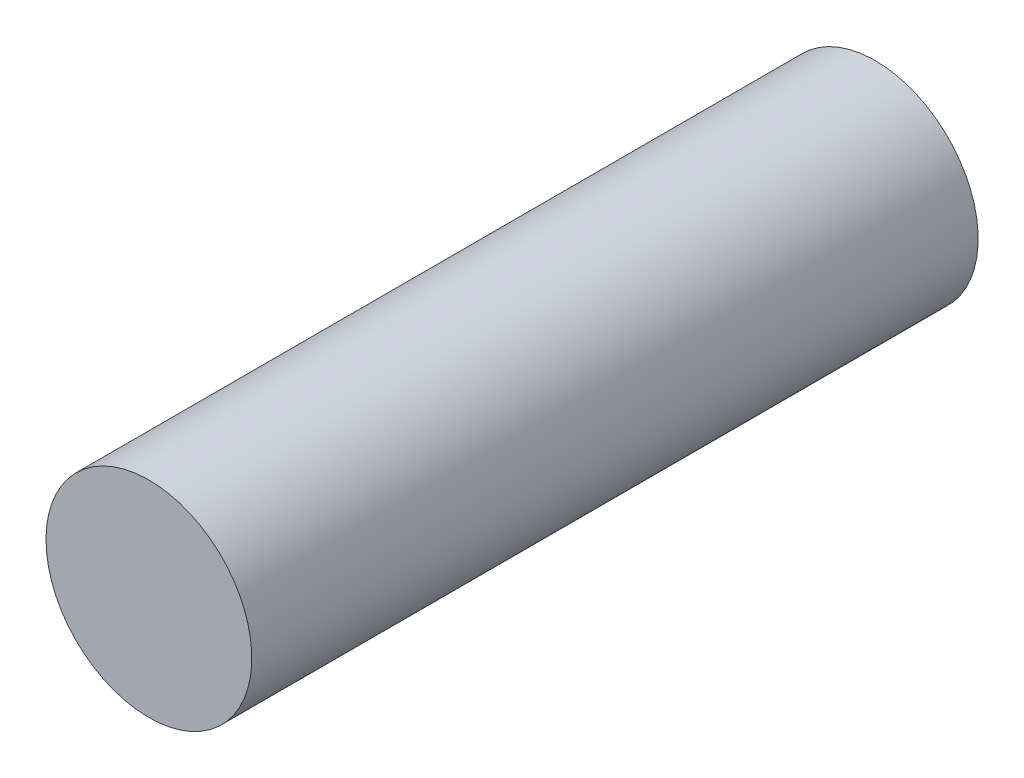
SolidWorks part; units mm, degrees
ref_plane "Front" through (0, 0, 0) normal (0, 0, 1) x (1, 0, 0)
ref_plane "Top" through (0, 0, 0) normal (0, 1, 0) x (1, 0, 0)
ref_plane "Right" through (0, 0, 0) normal (1, 0, 0) x (0, 0, -1)
sketch "Sketch1" plane through (0, 0, 0) normal (0, 0, 1) x (1, 0, 0)
  circle A0 centre (0, 0) radius 12.75
  dimension "D1" = 25.5
extrude "Extrude1" add sketch "Sketch1" along normal blind 90
